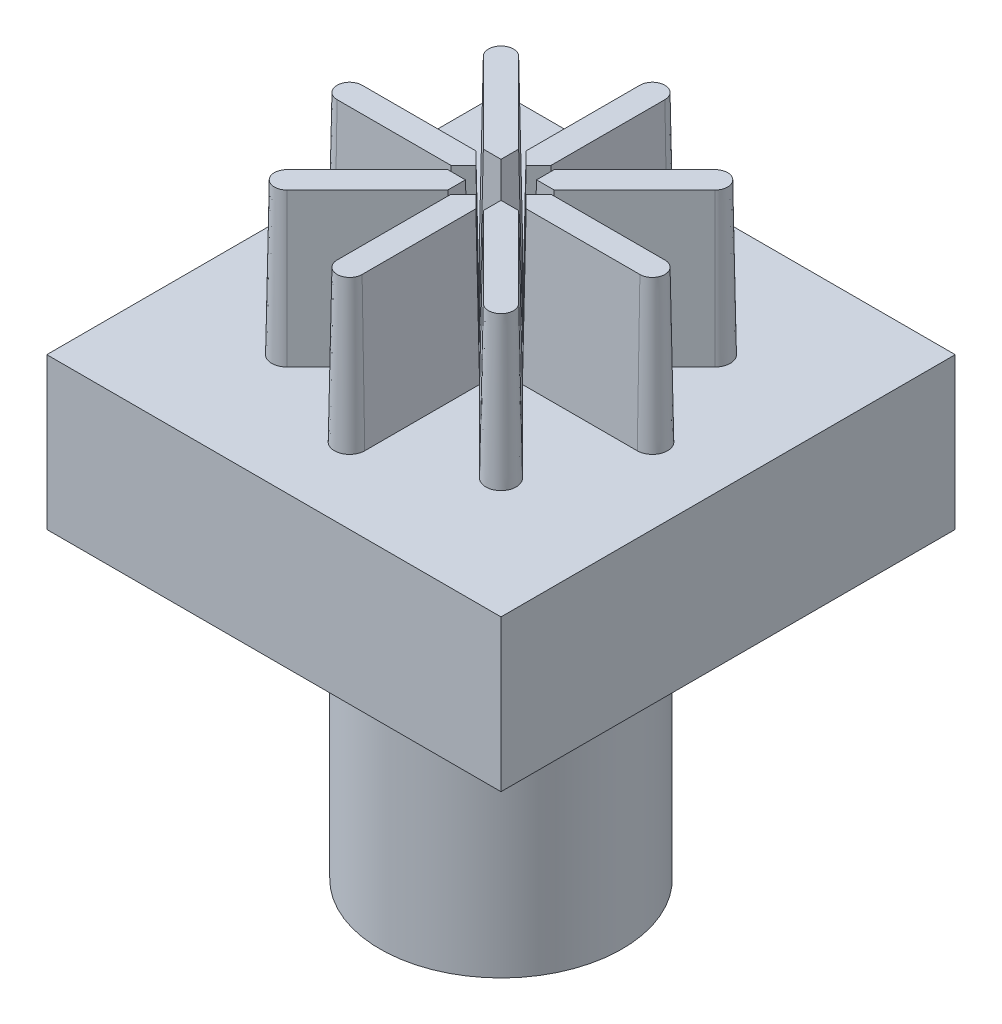
SolidWorks part; units mm, degrees
ref_plane "Front Plane" through (0, 0, 0) normal (0, 0, 1) x (1, 0, 0)
ref_plane "Top Plane" through (0, 0, 0) normal (0, 1, 0) x (1, 0, 0)
ref_plane "Right Plane" through (0, 0, 0) normal (1, 0, 0) x (0, 0, -1)
sketch "Sketch1" plane through (0, 0, 0) normal (0, 1, 0) x (1, 0, 0)
  line L1 (7.5, -7.5) -> (-7.5, -7.5)
  line L2 (7.5, -7.5) -> (7.5, 7.5)
  line L3 (7.5, 7.5) -> (-7.5, 7.5)
  line L4 (-7.5, -7.5) -> (-7.5, 7.5)
  line L5 (7.5, -7.5) -> (-7.5, 7.5) construction
  line L6 (7.5, 7.5) -> (-7.5, -7.5) construction
  point P0 (0, 0)
  dimension "D1" = 15
  dimension "D2" = 15
extrude "Boss-Extrude1" add sketch "Sketch1" along normal blind 5
sketch "Sketch2" plane through (0, 5, 0) normal (0, 1, 0) x (1, 0, 0)
  line L0 (0, -5) -> (0, 5) construction
  line L1 (-0.5, -5) -> (-0.5, 5)
  line L2 (0.5, -5) -> (0.5, 5)
  line L3 (-3.182, -3.8891) -> (3.8891, 3.182)
  line L4 (-3.8891, -3.182) -> (3.182, 3.8891)
  line L5 (-3.5355, -3.5355) -> (3.5355, 3.5355) construction
  line L6 (-5, -0.5) -> (5, -0.5)
  line L7 (0.4348, 0.5) -> (5, 0.5)
  line L8 (-5, 0) -> (5, 0) construction
  line L9 (-3.8891, 3.182) -> (3.182, -3.8891)
  line L10 (-3.182, 3.8891) -> (3.8891, -3.182)
  line L11 (-3.5355, 3.5355) -> (-0.5, 0.5) construction
  line L12 (-0.5, 5) -> (-0.5, 0.5)
  line L13 (0.5, 5) -> (0.5, -5)
  line L14 (0, 5) -> (0, -5) construction
  line L15 (3.182, 3.8891) -> (-3.8891, -3.182)
  line L16 (3.8891, 3.182) -> (-3.182, -3.8891)
  line L17 (3.5355, 3.5355) -> (-3.5355, -3.5355) construction
  line L18 (5, 0.5) -> (-5, 0.5)
  line L19 (5, -0.5) -> (-5, -0.5)
  line L20 (5, 0) -> (-5, 0) construction
  line L21 (3.8891, -3.182) -> (-3.182, 3.8891)
  line L22 (3.182, -3.8891) -> (-3.8891, 3.182)
  line L23 (3.5355, -3.5355) -> (-0.3536, 0.3536) construction
  line L24 (-0.5, 0.2071) -> (-0.5, -5)
  line L25 (-0.3536, 0.3536) -> (3.5355, -3.5355) construction
  arc A0 (-0.5, -5) -> (0.5, -5) centre (0, -5) ccw
  arc A1 (0.5, 5) -> (-0.5, 5) centre (0, 5) ccw
  arc A2 (-3.8891, -3.182) -> (-3.182, -3.8891) centre (-3.5355, -3.5355) ccw
  arc A3 (3.8891, 3.182) -> (3.182, 3.8891) centre (3.5355, 3.5355) ccw
  arc A4 (-5, 0.5) -> (-5, -0.5) centre (-5, 0) ccw
  arc A5 (5, -0.5) -> (5, 0.5) centre (5, 0) ccw
  arc A6 (-3.182, 3.8891) -> (-3.8891, 3.182) centre (-3.5355, 3.5355) ccw
  arc A7 (3.182, -3.8891) -> (3.8891, -3.182) centre (3.5355, -3.5355) ccw
  arc A8 (0.5, 5) -> (-0.5, 5) centre (0, 5) ccw
  arc A9 (-0.5, -5) -> (0.5, -5) centre (0, -5) ccw
  arc A10 (3.8891, 3.182) -> (3.182, 3.8891) centre (3.5355, 3.5355) ccw
  arc A11 (-3.8891, -3.182) -> (-3.182, -3.8891) centre (-3.5355, -3.5355) ccw
  arc A12 (5, -0.5) -> (5, 0.5) centre (5, 0) ccw
  arc A13 (-5, 0.5) -> (-5, -0.5) centre (-5, 0) ccw
  arc A14 (3.182, -3.8891) -> (3.8891, -3.182) centre (3.5355, -3.5355) ccw
  arc A15 (-3.182, 3.8891) -> (-3.8891, 3.182) centre (-3.5355, 3.5355) ccw
  point P2 (0, 0)
  point P13 (0, 0)
  point P20 (0, 0)
  point P27 (0, 0)
  point P34 (0, 0)
  point P41 (0, 0)
  point P48 (0, 0)
  point P55 (0, 0)
  point P60 (0, 0)
  dimension "D1" = 10
  dimension "D2" = 1
  dimension "D3" = 8
extrude "Boss-Extrude2" add sketch "Sketch2" along normal blind 5 draft 1 contours L2 A1 L1 L10 L4 | L3 A3 L4 L2 L7 | L6 A5 L7 L3 L10 | L9 A7 L10 L6 L2 | L1 A0 L2 L9 L3 | L4 A2 L3 L1 L6 | L18 A4 L6 L4 L9 | L10 A6 L9 L18 L1
sketch "Sketch3" plane through (0, 0, 0) normal (0, -1, 0) x (1, 0, 0)
  circle A0 centre (0, 0) radius 4
  dimension "D1" = 8
extrude "Boss-Extrude3" add sketch "Sketch3" along normal blind 10
equation "\"Connector_Dia\"= 8mm"
equation "\"Connector_height\"= 10mm"
equation "\"Base_Side\"= 15mm"
equation "\"Base_Thickness\"= 5mm"
equation "\"D1@Sketch3\"=\"Connector_Dia\""
equation "\"D1@Boss-Extrude3\"=\"Connector_height\""
equation "\"D1@Sketch1\"=\"Base_Side\""
equation "\"D2@Sketch1\"=\"Base_Side\""
equation "\"Ray_Length\"= 10mm"
equation "\"Ray_Width\"= 1mm"
equation "\"D2@Sketch2\"=\"Ray_Width\""
equation "\"D1@Sketch2\"=\"Ray_Length\""
